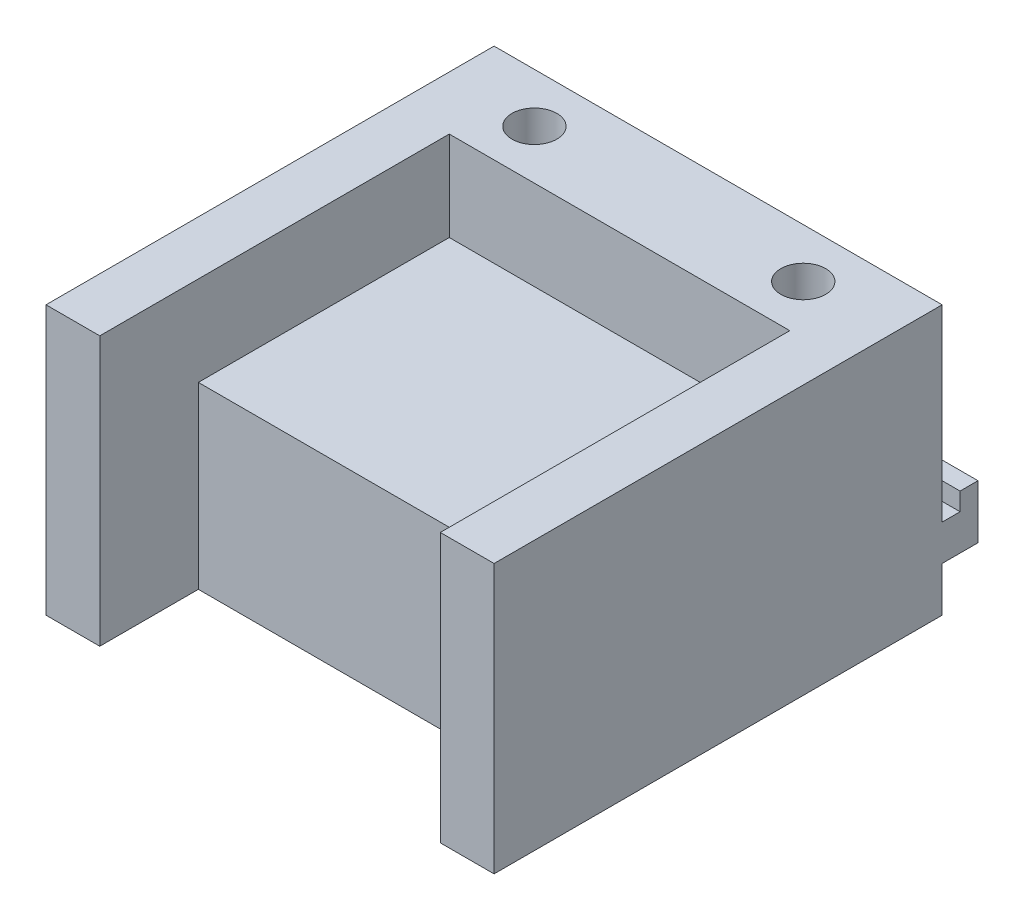
SolidWorks part; units mm, degrees
ref_plane "Front" through (0, 0, 0) normal (0, 0, 1) x (1, 0, 0)
ref_plane "Top" through (0, 0, 0) normal (0, 1, 0) x (1, 0, 0)
ref_plane "Right" through (0, 0, 0) normal (1, 0, 0) x (0, 0, -1)
sketch "Sketch1" plane through (0, 0, 0) normal (0, 1, 0) x (1, 0, 0)
  line L1 (-12.5, -12.5) -> (12.5, -12.5)
  line L2 (-12.5, -12.5) -> (-12.5, 12.5)
  line L3 (-12.5, 12.5) -> (12.5, 12.5)
  line L4 (12.5, -12.5) -> (12.5, 12.5)
  line L5 (-12.5, -12.5) -> (12.5, 12.5) construction
  line L6 (-12.5, 12.5) -> (12.5, -12.5) construction
  point P0 (0, 0)
  dimension "D1" = 25
  dimension "D2" = 25
extrude "Boss-Extrude1" add sketch "Sketch1" along normal blind 15
sketch "Sketch2" plane through (0, 15, 0) normal (0, 1, 0) x (1, 0, 0)
  line L1 (-9.5, -7) -> (9.5, -7)
  line L2 (-9.5, -7) -> (-9.5, 7)
  line L3 (-9.5, 7) -> (9.5, 7)
  line L4 (9.5, -7) -> (9.5, 7)
  line L5 (-9.5, -7) -> (9.5, 7) construction
  line L6 (-9.5, 7) -> (9.5, -7) construction
  point P0 (0, 0)
  dimension "D1" = 19
  dimension "D2" = 14
extrude "Cut-Extrude1" cut sketch "Sketch2" against normal blind 5
sketch "Sketch3" plane through (0, 15, 0) normal (0, 1, 0) x (1, 0, 0)
  line L0 (-9.5, -7) -> (-9.5, -12.5)
  line L1 (9.5, -7) -> (9.5, -12.5)
  line L2 (-12.5, -12.5) -> (12.5, -12.5) construction
extrude "Cut-Extrude2" cut sketch "Sketch3" against normal blind 15 and the other way through all
sketch "Sketch4" plane through (0, 15, 0) normal (0, 1, 0) x (1, 0, 0)
  line L0 (-12.5, 9.75) -> (12.5, 9.75) construction
  line L1 (-12.5, 12.5) -> (-12.5, -12.5) construction
  line L2 (12.5, -12.5) -> (12.5, 12.5) construction
  line L3 (0, 7) -> (0, 12.5) construction
  line L4 (9.5, 7) -> (-9.5, 7) construction
  line L5 (12.5, 12.5) -> (-12.5, 12.5) construction
  point P6 (-7.5, 9.75)
  point P7 (7.5, 9.75)
  point P14 (0, 9.75)
  dimension "D1" = 5
  dimension "D2" = 5
hole_wizard "Tap Drill for M3x0.5 Tap1" positions "3DSketch2" profile "Sketch5" hole size "M3x0.5" standard "ANSI Metric"
sketch3d "3DSketch2"
  point P0 (-7.5, 15, -9.75)
  point P3 (7.5, 15, -9.75)
sketch "Sketch5" plane through (-7.5, 15, -9.75) normal (1, 0, 0) x (0, 0, 1)
  line L0 (0, 0) -> (0, 5.7511)
  line L1 (0, 5.7511) -> (1.25, 5)
  line L2 (1.25, 5) -> (1.25, 0)
  line L5 (1.25, 0) -> (0, 0)
  line L10 (0, 5.7511) -> (-1.25, 5) construction
  line L11 (0, -6.35) -> (0, 107.95) construction
  dimension "Hole Dia." = 2.5
  dimension "Hole Depth" = 5
  dimension "Drill Angle" = 118
sketch "Sketch6" plane through (12.5, 0, 0) normal (1, 0, 0) x (0, 0, -1)
  line L5 (12.5, 15) -> (12.5, 0) construction
  line L10 (12.5, 2.5) -> (14.5, 2.5)
  line L11 (12.5, 2.5) -> (12.5, 4.5)
  line L12 (12.5, 4.5) -> (14.5, 4.5)
  line L13 (14.5, 2.5) -> (14.5, 4.5)
  line L14 (-12.5, 0) -> (12.5, 0) construction
  dimension "D1" = 2
  dimension "D2" = 2
  dimension "D3" = 2.5
extrude "Boss-Extrude2" add sketch "Sketch6" against normal up to surface (25 mm away) up to face at (-12.5, 7.5, 0)
sketch "Sketch7" plane through (12.5, 0, 0) normal (1, 0, 0) x (0, 0, -1)
  line L6 (14.5, 4.5) -> (12.5, 4.5) construction
  line L8 (13.5, 4.5) -> (14.5, 4.5)
  line L9 (13.5, 4.5) -> (13.5, 5.5)
  line L10 (13.5, 5.5) -> (14.5, 5.5)
  line L11 (14.5, 4.5) -> (14.5, 5.5)
  line L12 (14.5, 2.5) -> (14.5, 4.5) construction
  dimension "D1" = 1
  dimension "D2" = 0
  dimension "D3" = 1
extrude "Boss-Extrude3" add sketch "Sketch7" against normal up to surface (25 mm away) up to face at (-12.5, 5.5, -6.75)
